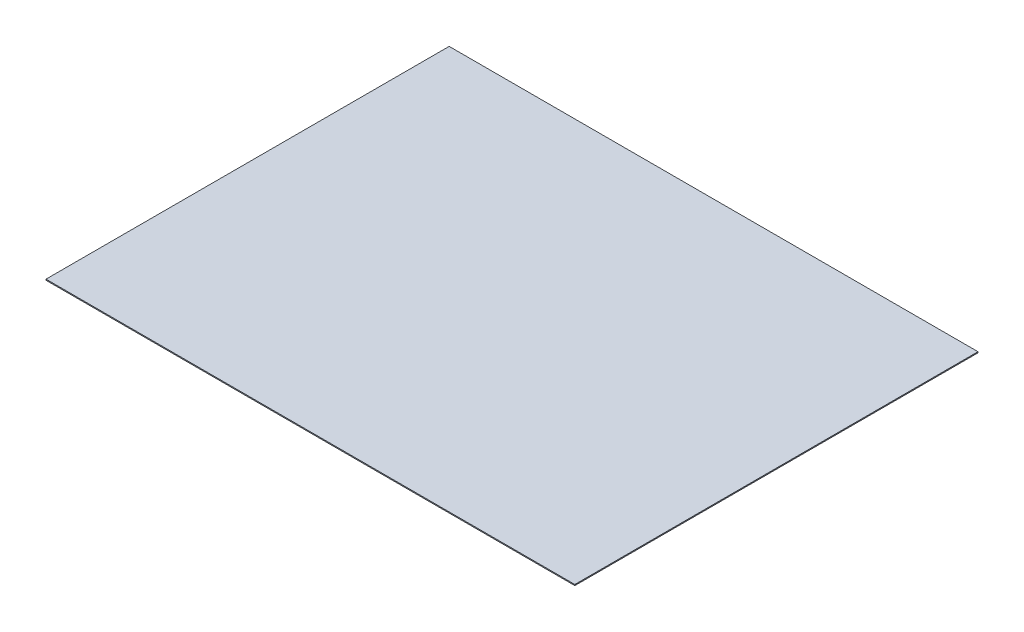
SolidWorks part; units mm, degrees
ref_plane "Alzado" through (0, 0, 0) normal (0, 0, 1) x (1, 0, 0)
ref_plane "Planta" through (0, 0, 0) normal (0, 1, 0) x (1, 0, 0)
ref_plane "Vista lateral" through (0, 0, 0) normal (1, 0, 0) x (0, 0, -1)
sketch "Croquis1" plane through (0, 0, 0) normal (0, 1, 0) x (1, 0, 0)
  line L1 (0, 0) -> (1519.3, 0)
  line L2 (0, 0) -> (0, -1158.2)
  line L3 (0, -1158.2) -> (1519.3, -1158.2)
  line L4 (1519.3, 0) -> (1519.3, -1158.2)
  dimension "D1" = 1158.2
  dimension "D2" = 1519.3
extrude "Saliente-Extruir1" add sketch "Croquis1" along normal blind 2.9
